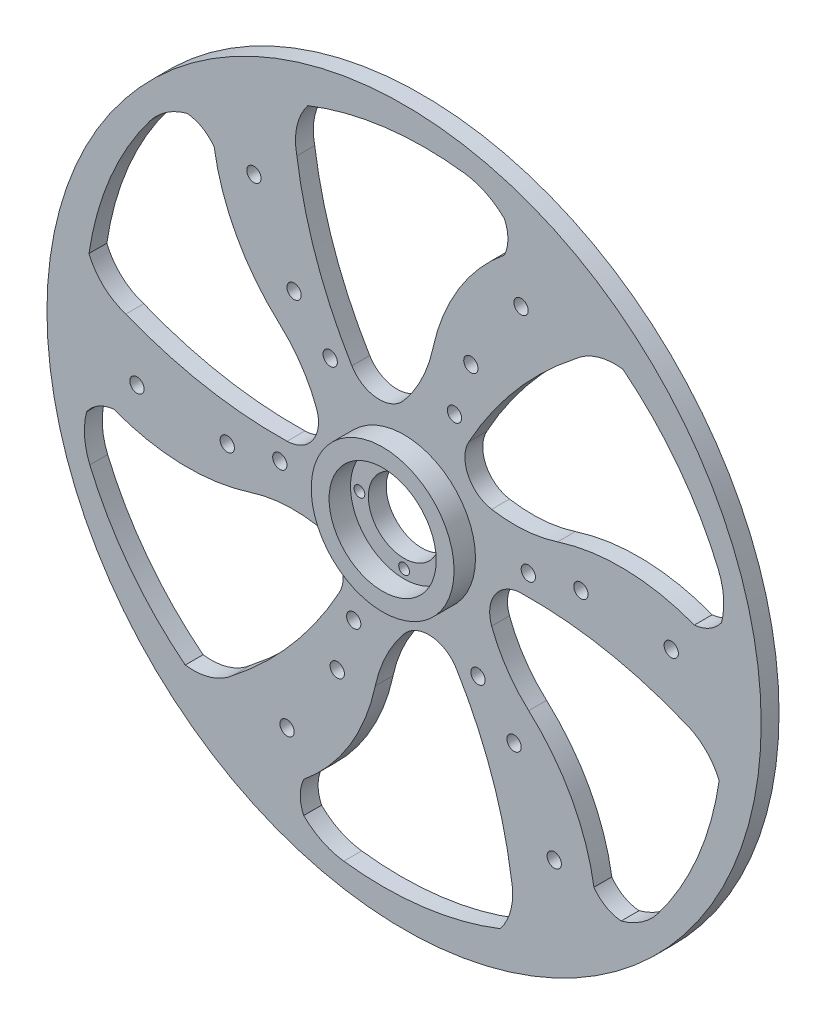
SolidWorks part; units mm, degrees
ref_plane "Front Plane" through (0, 0, 0) normal (0, 0, 1) x (1, 0, 0)
ref_plane "Top Plane" through (0, 0, 0) normal (0, 1, 0) x (1, 0, 0)
ref_plane "Right Plane" through (0, 0, 0) normal (1, 0, 0) x (0, 0, -1)
sketch "Sketch1" plane through (0, 0, 0) normal (0, 0, 1) x (1, 0, 0)
  line L0 (0, 0) -> (0, 143.4096) construction
  circle A0 centre (0, 0) radius 100
  circle A2 centre (0, 0) radius 50 construction
  arc A10 (-14.6269, 29.3913) -> (-6.4652, 25.0686) centre (-6.9325, 34.0527) ccw
  arc A11 (-6.4652, 25.0686) -> (0, 28.3193) centre (-6.9325, 34.0527) ccw
  arc A12 (0, 28.3193) -> (8.068, 44.9658) centre (-30.0218, 53.1482) ccw
  arc A13 (8.068, 44.9658) -> (28.1054, 77.6242) centre (64.4375, 32.8567) cw
  arc A14 (28.1054, 77.6242) -> (28.1054, 86.4087) centre (18.6277, 82.0164) ccw
  arc A15 (28.1054, 86.4087) -> (22.5623, 90.2462) centre (14.4626, 72.6245) ccw
  arc A16 (22.5623, 90.2462) -> (16.8767, 91.8677) centre (14.4626, 72.6245) ccw
  arc A17 (16.8767, 91.8677) -> (-26.9489, 86.3224) centre (5.7925, 3.5151) ccw
  arc A18 (-26.9489, 86.3224) -> (-30.0218, 72.6245) centre (-13.8887, 76.199) ccw
  arc A19 (-30.0218, 72.6245) -> (-14.6269, 29.3913) centre (82.9123, 88.4816) ccw
  circle A20 centre (0, 0) radius 15
  circle A71 centre (0, 0) radius 35 construction
  circle A72 centre (0, 0) radius 75 construction
  circle A73 centre (18.7062, 46.3689) radius 2
  circle A74 centre (14.1004, 32.034) radius 2
  circle A75 centre (32.7671, 67.4635) radius 2
  arc A76 (47.8838, 62.3119) -> (18.1402, 27.3629) centre (118.0834, -27.5633) ccw
  arc A77 (18.1402, 27.3629) -> (18.4775, 18.1333) centre (26.0242, 23.0301) ccw
  arc A78 (18.4775, 18.1333) -> (24.5252, 14.1596) centre (26.0242, 23.0301) ccw
  arc A79 (24.5252, 14.1596) -> (42.9756, 15.4958) centre (31.0168, 52.5737) ccw
  arc A80 (42.9756, 15.4958) -> (81.2772, 14.4721) centre (60.6735, -39.3762) cw
  arc A81 (81.2772, 14.4721) -> (88.8848, 18.8644) centre (80.3422, 24.8761) ccw
  arc A82 (88.8848, 18.8644) -> (89.4367, 25.5836) centre (70.1259, 23.7873) ccw
  arc A83 (89.4367, 25.5836) -> (87.9982, 31.3182) centre (70.1259, 23.7873) ccw
  arc A84 (87.9982, 31.3182) -> (61.283, 66.4996) centre (5.9404, -3.2589) ccw
  arc A85 (61.283, 66.4996) -> (47.8838, 62.3119) centre (59.0459, 50.1275) ccw
  circle A86 centre (34.7925, 3.8057) radius 2
  circle A87 centre (49.5098, 6.9844) radius 2
  circle A88 centre (74.8086, 5.3546) radius 2
  arc A89 (77.9055, -10.3126) -> (32.7671, -2.0284) centre (35.1712, -116.0449) ccw
  arc A90 (32.7671, -2.0284) -> (24.9427, -6.9353) centre (32.9567, -11.0226) ccw
  arc A91 (24.9427, -6.9353) -> (24.5252, -14.1596) centre (32.9567, -11.0226) ccw
  arc A92 (24.5252, -14.1596) -> (34.9076, -29.47) centre (61.0386, -0.5745) ccw
  arc A93 (34.9076, -29.47) -> (53.1718, -63.1521) centre (-3.7641, -72.2329) cw
  arc A94 (53.1718, -63.1521) -> (60.7794, -67.5443) centre (61.7145, -57.1403) ccw
  arc A95 (60.7794, -67.5443) -> (66.8744, -64.6626) centre (55.6634, -48.8372) ccw
  arc A96 (66.8744, -64.6626) -> (71.1215, -60.5495) centre (55.6634, -48.8372) ccw
  arc A97 (71.1215, -60.5495) -> (88.2319, -19.8228) centre (0.148, -6.774) ccw
  arc A98 (88.2319, -19.8228) -> (77.9055, -10.3126) centre (72.9346, -26.0715) ccw
  circle A99 centre (20.692, -28.2283) radius 2
  circle A100 centre (30.8036, -39.3845) radius 2
  circle A101 centre (42.0415, -62.1089) radius 2
  arc A102 (30.0218, -72.6245) -> (14.6269, -29.3913) centre (-82.9123, -88.4816) ccw
  arc A103 (14.6269, -29.3913) -> (6.4652, -25.0686) centre (6.9325, -34.0527) ccw
  arc A104 (6.4652, -25.0686) -> (0, -28.3193) centre (6.9325, -34.0527) ccw
  arc A105 (0, -28.3193) -> (-8.068, -44.9658) centre (30.0218, -53.1482) ccw
  arc A106 (-8.068, -44.9658) -> (-28.1054, -77.6242) centre (-64.4375, -32.8567) cw
  arc A107 (-28.1054, -77.6242) -> (-28.1054, -86.4087) centre (-18.6277, -82.0164) ccw
  arc A108 (-28.1054, -86.4087) -> (-22.5623, -90.2462) centre (-14.4626, -72.6245) ccw
  arc A109 (-22.5623, -90.2462) -> (-16.8767, -91.8677) centre (-14.4626, -72.6245) ccw
  arc A110 (-16.8767, -91.8677) -> (26.9489, -86.3224) centre (-5.7925, -3.5151) ccw
  arc A111 (26.9489, -86.3224) -> (30.0218, -72.6245) centre (13.8887, -76.199) ccw
  circle A112 centre (-14.1004, -32.034) radius 2
  circle A113 centre (-18.7062, -46.3689) radius 2
  circle A114 centre (-32.7671, -67.4635) radius 2
  arc A115 (-47.8838, -62.3119) -> (-18.1402, -27.3629) centre (-118.0834, 27.5633) ccw
  arc A116 (-18.1402, -27.3629) -> (-18.4775, -18.1333) centre (-26.0242, -23.0301) ccw
  arc A117 (-18.4775, -18.1333) -> (-24.5252, -14.1596) centre (-26.0242, -23.0301) ccw
  arc A118 (-24.5252, -14.1596) -> (-42.9756, -15.4958) centre (-31.0168, -52.5737) ccw
  arc A119 (-42.9756, -15.4958) -> (-81.2772, -14.4721) centre (-60.6735, 39.3762) cw
  arc A120 (-81.2772, -14.4721) -> (-88.8848, -18.8644) centre (-80.3422, -24.8761) ccw
  arc A121 (-88.8848, -18.8644) -> (-89.4367, -25.5836) centre (-70.1259, -23.7873) ccw
  arc A122 (-89.4367, -25.5836) -> (-87.9982, -31.3182) centre (-70.1259, -23.7873) ccw
  arc A123 (-87.9982, -31.3182) -> (-61.283, -66.4996) centre (-5.9404, 3.2589) ccw
  arc A124 (-61.283, -66.4996) -> (-47.8838, -62.3119) centre (-59.0459, -50.1275) ccw
  circle A125 centre (-34.7925, -3.8057) radius 2
  circle A126 centre (-49.5098, -6.9844) radius 2
  circle A127 centre (-74.8086, -5.3546) radius 2
  arc A128 (-77.9055, 10.3126) -> (-32.7671, 2.0284) centre (-35.1712, 116.0449) ccw
  arc A129 (-32.7671, 2.0284) -> (-24.9427, 6.9353) centre (-32.9567, 11.0226) ccw
  arc A130 (-24.9427, 6.9353) -> (-24.5252, 14.1596) centre (-32.9567, 11.0226) ccw
  arc A131 (-24.5252, 14.1596) -> (-34.9076, 29.47) centre (-61.0386, 0.5745) ccw
  arc A132 (-34.9076, 29.47) -> (-53.1718, 63.1521) centre (3.7641, 72.2329) cw
  arc A133 (-53.1718, 63.1521) -> (-60.7794, 67.5443) centre (-61.7145, 57.1403) ccw
  arc A134 (-60.7794, 67.5443) -> (-66.8744, 64.6626) centre (-55.6634, 48.8372) ccw
  arc A135 (-66.8744, 64.6626) -> (-71.1215, 60.5495) centre (-55.6634, 48.8372) ccw
  arc A136 (-71.1215, 60.5495) -> (-88.2319, 19.8228) centre (-0.148, 6.774) ccw
  arc A137 (-88.2319, 19.8228) -> (-77.9055, 10.3126) centre (-72.9346, 26.0715) ccw
  circle A138 centre (-20.692, 28.2283) radius 2
  circle A139 centre (-30.8036, 39.3845) radius 2
  circle A140 centre (-42.0415, 62.1089) radius 2
  circle A141 centre (0, 0) radius 10
  circle A142 centre (0, 0) radius 5
  spline S0 degree 3 poles (0, 0) (16.5572, 20.1956) (12.1395, 49.705) (32.7671, 67.4635) knots 0 0 0 0 1 1 1 1 construction
  point P130 (0, 0)
  point P171 (0, 0)
  dimension "D1" = 200
  dimension "D2" = 100
  dimension "D3" = 30
  dimension "D5" = 70
  dimension "D6" = 150
  dimension "D7" = 4
  dimension "D8" = 4
  dimension "D9" = 4
  dimension "D10" = 20
  dimension "D11" = 10
  dimension "D4" = 6
extrude "Boss-Extrude1" add sketch "Sketch1" along normal blind 5
sketch "Sketch2" plane through (0, 0, 5) normal (0, 0, 1) x (1, 0, 0)
  circle A0 centre (0, 0) radius 20
  circle A1 centre (0, 0) radius 15
  dimension "D1" = 40
extrude "Boss-Extrude2" add sketch "Sketch2" along normal blind 6
sketch "Sketch3" plane through (0, 0, 5) normal (0, 0, 1) x (1, 0, 0)
  circle A0 centre (0, 12.5) radius 1.5
  circle A1 centre (12.5, 0) radius 1.5
  circle A2 centre (0, -12.5) radius 1.5
  circle A3 centre (-12.5, 0) radius 1.5
  point P12 (0, 0)
  dimension "D1" = 3
  dimension "D2" = 12.5
  dimension "D3" = 4
extrude "Cut-Extrude1" cut sketch "Sketch3" against normal up to next
equation "\"30、\"=5"
